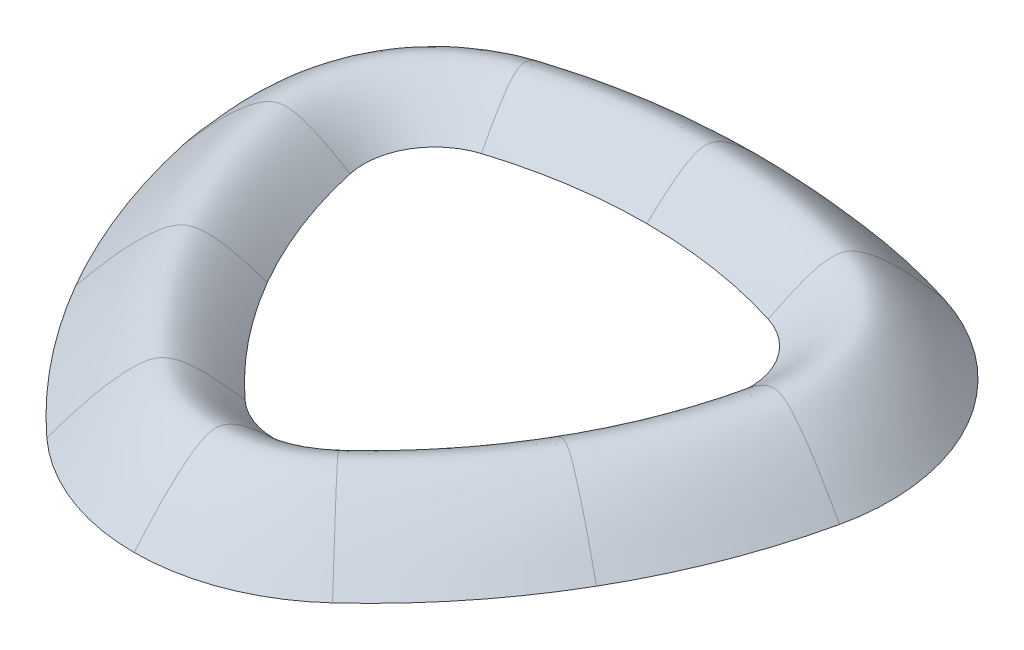
SolidWorks part; units mm, degrees
ref_plane "Plan de face" through (0, 0, 0) normal (0, 0, 1) x (1, 0, 0)
ref_plane "Plan de dessus" through (0, 0, 0) normal (0, 1, 0) x (1, 0, 0)
ref_plane "Plan de droite" through (0, 0, 0) normal (1, 0, 0) x (0, 0, -1)
ref_plane "Plan3" through (0, 110, 0) normal (0, 1, 0) x (-1, 0, 0)
ref_plane "Plan4" through (17.1, 0, 0) normal (1, 0, 0) x (0, 0, -1)
sketch "Esquisse2" plane through (0, 110, 0) normal (0, 1, 0) x (1, 0, 0)
  line L6 (-8.1531, -15.9216) -> (-19.8444, -22.6716)
  line L7 (54.0497, -22.6716) -> (42.3584, -15.9216)
  arc A10 (17.1026, 27.8226) -> (-5.1741, 24.3979) centre (17.1026, -46.3402) ccw
  arc A11 (17.1026, 41.3226) -> (-9.2291, 37.2745) centre (17.1026, -46.3402) ccw
  arc A12 (-9.2291, 37.2745) -> (-29.5045, 2.1565) centre (-0.2179, 8.6598) ccw
  arc A13 (-29.5045, 2.1565) -> (-19.8444, -22.6716) centre (56.0737, 21.1599) ccw
  arc A14 (-16.3255, 5.083) -> (-8.1531, -15.9216) centre (56.0738, 21.1598) ccw
  arc A15 (-5.1741, 24.3979) -> (-16.3255, 5.083) centre (-0.2179, 8.6598) ccw
  arc A16 (-8.1531, -15.9216) -> (5.9512, -33.5014) centre (56.0738, 21.1598) ccw
  arc A17 (-19.8444, -22.6716) -> (-3.1727, -43.4515) centre (56.0738, 21.1598) ccw
  arc A18 (-3.1727, -43.4515) -> (37.378, -43.4515) centre (17.1026, -21.3402) ccw
  arc A19 (37.378, -43.4515) -> (54.0497, -22.6716) centre (-21.8686, 21.1598) ccw
  arc A20 (28.2541, -33.5014) -> (42.3584, -15.9216) centre (-21.8685, 21.1598) ccw
  arc A21 (5.9512, -33.5014) -> (28.2541, -33.5014) centre (17.1026, -21.3402) ccw
  arc A22 (-8.1531, -15.9216) -> (5.9512, -33.5014) centre (56.0738, 21.1598) ccw
  arc A23 (-19.8444, -22.6716) -> (-3.1727, -43.4515) centre (56.0738, 21.1598) ccw
  arc A24 (-3.1727, -43.4515) -> (37.378, -43.4515) centre (17.1026, -21.3402) ccw
  arc A25 (37.378, -43.4515) -> (54.0497, -22.6716) centre (-21.8686, 21.1598) ccw
  arc A26 (28.2541, -33.5014) -> (42.3584, -15.9216) centre (-21.8685, 21.1598) ccw
  arc A27 (5.9512, -33.5014) -> (28.2541, -33.5014) centre (17.1026, -21.3402) ccw
  arc A34 (42.3584, -15.9216) -> (50.5308, 5.083) centre (-21.8685, 21.1598) ccw
  arc A35 (54.0497, -22.6716) -> (63.7098, 2.1564) centre (-21.8685, 21.1599) ccw
  arc A36 (63.7098, 2.1564) -> (43.4344, 37.2745) centre (34.4231, 8.6598) ccw
  arc A37 (43.4344, 37.2745) -> (17.1026, 41.3226) centre (17.1027, -46.3402) ccw
  arc A38 (39.3793, 24.3979) -> (17.1026, 27.8226) centre (17.1026, -46.3402) ccw
  arc A39 (50.5308, 5.083) -> (39.3793, 24.3979) centre (34.4231, 8.6598) ccw
  spline S1 degree 3 poles (17.1026, -35.3402) (17.2945, -35.3402) (17.585, -35.3335) (17.9697, -35.3151) (18.3296, -35.2878) (18.5783, -35.2628) (19.4384, -35.1634) (20.8852, -34.8799) (22.9641, -34.1179) (24.8892, -33.0438) (26.0338, -32.1454) (28.4344, -29.9441) (32.0049, -26.3034) (36.7478, -20.302) (40.7972, -13.8767) (43.0004, -9.3962) (44.4388, -6.0483) (45.2663, -3.9788) (46.3263, -0.9419) (47.2595, 2.173) (47.8205, 4.4103) (48.2248, 6.231) (48.4333, 7.5487) (48.4428, 9.8236) (48.0342, 12.2266) (47.5021, 13.7089) (46.7937, 15.2889) (45.7554, 17.0831) (43.583, 19.3997) (41.0947, 21.0774) (39.4318, 21.7603) (36.0835, 22.8148) (31.0227, 24.0976) (23.5051, 25.1675) (16.0545, 25.4426) (11.1305, 25.116) (7.5119, 24.6877) (5.3059, 24.3696) (2.1458, 23.7691) (-1.0183, 23.0198) (-3.2364, 22.387) (-5.0153, 21.8268) (-6.2607, 21.3486) (-8.2356, 20.2193) (-10.1123, 18.664) (-11.13, 17.4621) (-12.1441, 16.0585) (-13.1788, 14.2622) (-14.0988, 11.2226) (-14.3076, 8.2288) (-14.0676, 6.4472) (-13.3066, 3.0202) (-11.8871, -2.0039) (-9.0549, -9.0493) (-5.5678, -15.6392) (-2.823, -19.7403) (-0.6428, -22.66) (0.7092, -24.3765) (2.7496, -26.7512) (4.9491, -29.0929) (6.6373, -30.7387) (8.0998, -32.0796) (8.9058, -32.7376) (10.3234, -33.6134) (11.5706, -34.228) (12.9719, -34.7458) (14.4341, -35.1099) (15.8425, -35.3053) (16.6985, -35.3402) (17.1026, -35.3402) (17.2945, -35.3402) (17.585, -35.3335) knots -0.004472 0 0 0 0.002123 0.004246 0.006369 0.008493 0.008493 0.020144 0.031796 0.043448 0.0551 0.0551 0.096159 0.137217 0.178275 0.219334 0.219334 0.238889 0.258444 0.277999 0.297554 0.297554 0.307313 0.317071 0.326829 0.336587 0.336587 0.349549 0.36251 0.375472 0.388433 0.388433 0.429492 0.47055 0.511609 0.552667 0.552667 0.572222 0.591777 0.611333 0.630888 0.630888 0.640646 0.650404 0.660162 0.66992 0.66992 0.682882 0.695844 0.708805 0.721767 0.721767 0.762825 0.803884 0.844942 0.886 0.886 0.905556 0.925111 0.944666 0.964221 0.964221 0.973166 0.977638 0.982111 0.986583 0.991055 0.995528 1 1 1 1.002123 1.004246 1.006369 only from (17.1026, -35.3402) to (17.1026, -35.3402)
  spline S2 degree 3 poles (17.1026, -35.3402) (17.2945, -35.3402) (17.585, -35.3335) (17.9697, -35.3151) (18.3296, -35.2878) (18.5783, -35.2628) (19.4384, -35.1634) (20.8852, -34.8799) (22.9641, -34.1179) (24.8892, -33.0438) (26.0338, -32.1454) (28.4344, -29.9441) (32.0049, -26.3034) (36.7478, -20.302) (40.7972, -13.8767) (43.0004, -9.3962) (44.4388, -6.0483) (45.2663, -3.9788) (46.3263, -0.9419) (47.2595, 2.173) (47.8205, 4.4103) (48.2248, 6.231) (48.4333, 7.5487) (48.4428, 9.8236) (48.0342, 12.2266) (47.5021, 13.7089) (46.7937, 15.2889) (45.7554, 17.0831) (43.583, 19.3997) (41.0947, 21.0774) (39.4318, 21.7603) (36.0835, 22.8148) (31.0227, 24.0976) (23.5051, 25.1675) (16.0545, 25.4426) (11.1305, 25.116) (7.5119, 24.6877) (5.3059, 24.3696) (2.1458, 23.7691) (-1.0183, 23.0198) (-3.2364, 22.387) (-5.0153, 21.8268) (-6.2607, 21.3486) (-8.2356, 20.2193) (-10.1123, 18.664) (-11.13, 17.4621) (-12.1441, 16.0585) (-13.1788, 14.2622) (-14.0988, 11.2226) (-14.3076, 8.2288) (-14.0676, 6.4472) (-13.3066, 3.0202) (-11.8871, -2.0039) (-9.0549, -9.0493) (-5.5678, -15.6392) (-2.823, -19.7403) (-0.6428, -22.66) (0.7092, -24.3765) (2.7496, -26.7512) (4.9491, -29.0929) (6.6373, -30.7387) (8.0998, -32.0796) (8.9058, -32.7376) (10.3234, -33.6134) (11.5706, -34.228) (12.9719, -34.7458) (14.4341, -35.1099) (15.8425, -35.3053) (16.6985, -35.3402) (17.1026, -35.3402) (17.2945, -35.3402) (17.585, -35.3335) knots -0.004472 0 0 0 0.002123 0.004246 0.006369 0.008493 0.008493 0.020144 0.031796 0.043448 0.0551 0.0551 0.096159 0.137217 0.178275 0.219334 0.219334 0.238889 0.258444 0.277999 0.297554 0.297554 0.307313 0.317071 0.326829 0.336587 0.336587 0.349549 0.36251 0.375472 0.388433 0.388433 0.429492 0.47055 0.511609 0.552667 0.552667 0.572222 0.591777 0.611333 0.630888 0.630888 0.640646 0.650404 0.660162 0.66992 0.66992 0.682882 0.695844 0.708805 0.721767 0.721767 0.762825 0.803884 0.844942 0.886 0.886 0.905556 0.925111 0.944666 0.964221 0.964221 0.973166 0.977638 0.982111 0.986583 0.991055 0.995528 1 1 1 1.002123 1.004246 1.006369 only from (17.1026, -35.3402) to (17.1026, -35.3402)
  dimension "D2" = 0
  dimension "D4" = 0
sketch "Esquisse5" plane through (17.1, 0, 0) normal (-1, 0, 0) x (0, 0, 1)
  line L0 (-23.3226, 108) -> (-23.3226, 114) construction
  line L1 (-23.3226, 108) -> (-23.3226, 114)
  line L3 (-27.8226, 110) -> (-41.3226, 110)
  line L4 (-27.8226, 114) -> (-23.3226, 114) construction
  line L5 (-27.8226, 114) -> (-23.3226, 114)
  line L6 (51.3402, 110) -> (43.4515, 110) construction
  line L7 (51.3402, 110) -> (42.3402, 110)
  line L8 (37.8402, 110) -> (37.8402, 114) construction
  line L9 (37.8402, 110) -> (37.8402, 114)
  line L10 (-27.8226, 114) -> (-27.8226, 110)
  line L11 (42.3402, 114) -> (42.3402, 110)
  line L12 (42.3402, 114) -> (37.8402, 114)
  spline S0 degree 3 poles (-54903.5092, 51079.9374) (1466.9212, 138.1037) (314.7075, 473.5475) (-48.8728, 102.3988) (-50.7257, 100.4676) (-56.2112, 94.6088) (-59.7712, 90.6164) (-64.9306, 84.467) (-66.6203, 82.3903) (-69.9324, 78.1769) (-71.5567, 76.0374) (-76.2949, 69.5463) (-79.2784, 65.1194) (-84.8072, 56.0168) (-87.3535, 51.3417) (-90.7454, 44.0864) (-91.8043, 41.6272) (-93.2672, 37.8672) (-93.7345, 36.5996) (-94.6163, 34.0604) (-95.0316, 32.7869) (-96.9739, 26.3991) (-98.1012, 21.224) (-98.8575, 14.6561) (-98.976, 13.3376) (-99.1434, 10.6899) (-99.1897, 9.3604) (-101.9345, -200.5305) (529.2263, -505.3387) (-74247.296, 10639.9451) knots -12.002945 -12.002945 -12.002945 -12.002945 0.0625 0.0625 0.125 0.125 0.25 0.25 0.3125 0.3125 0.375 0.375 0.5 0.5 0.625 0.625 0.6875 0.6875 0.71875 0.71875 0.75 0.75 0.875 0.875 0.90625 0.90625 0.9375 0.9375 5.823478 5.823478 5.823478 5.823478 only from (-41.3226, 110) to (-99.1598, 0) construction
  spline S1 degree 3 poles (-41.3226, 110) (-43.2306, 108.1179) (-45.1255, 106.2242) (-48.8728, 102.3988) (-50.7257, 100.4676) (-56.2112, 94.6088) (-59.7712, 90.6164) (-64.9306, 84.467) (-66.6203, 82.3903) (-69.9324, 78.1769) (-71.5567, 76.0374) (-76.2949, 69.5463) (-79.2784, 65.1194) (-84.8072, 56.0168) (-87.3535, 51.3417) (-90.7454, 44.0864) (-91.8043, 41.6272) (-93.2672, 37.8672) (-93.7345, 36.5996) (-94.6163, 34.0604) (-95.0316, 32.7869) (-96.9739, 26.3991) (-98.1012, 21.224) (-98.8575, 14.6561) (-98.976, 13.3376) (-99.1434, 10.6899) (-99.1897, 9.3604) (-99.2421, 5.3587) (-99.1732, 2.6751) (-99.1598, 0) knots 0 0 0 0 0.0625 0.0625 0.125 0.125 0.25 0.25 0.3125 0.3125 0.375 0.375 0.5 0.5 0.625 0.625 0.6875 0.6875 0.71875 0.71875 0.75 0.75 0.875 0.875 0.90625 0.90625 0.9375 0.9375 1 1 1 1
  spline S2 degree 3 poles (-74498.6912, 8557.5283) (799.587, -513.4988) (-105.4428, -195.3689) (-97.0461, 12.7934) (-96.8063, 15.3415) (-96.0811, 20.4073) (-95.5957, 22.9251) (-94.7005, 26.6811) (-94.3743, 27.9297) (-93.6684, 30.4203) (-93.2885, 31.6628) (-91.2812, 37.8039) (-89.3211, 42.5387) (-84.8745, 51.7438) (-82.3865, 56.2133) (-78.3432, 62.7612) (-76.9432, 64.9175) (-74.7726, 68.1165) (-74.0372, 69.1772) (-72.5486, 71.2806) (-71.795, 72.3243) (-67.9828, 77.5045) (-64.7929, 81.5279) (-58.189, 89.3814) (-54.7744, 93.2111) (-49.5151, 98.8372) (-47.7389, 100.6927) (325.3347, 482.5877) (1557.7633, 120.2822) (-55711.5333, 50189.8675) knots -4.947507 -4.947507 -4.947507 -4.947507 0.0625 0.0625 0.125 0.125 0.1875 0.1875 0.21875 0.21875 0.25 0.25 0.375 0.375 0.5 0.5 0.5625 0.5625 0.59375 0.59375 0.625 0.625 0.75 0.75 0.875 0.875 0.9375 0.9375 13.85816 13.85816 13.85816 13.85816 only from (-97.1833, 2.5) to (-40.5014, 108) construction
  spline S3 degree 3 poles (-97.1833, 2.5) (-97.2144, 5.0814) (-97.253, 7.6638) (-97.0461, 12.7934) (-96.8063, 15.3415) (-96.0811, 20.4073) (-95.5957, 22.9251) (-94.7005, 26.6811) (-94.3743, 27.9297) (-93.6684, 30.4203) (-93.2885, 31.6628) (-91.2812, 37.8039) (-89.3211, 42.5387) (-84.8745, 51.7438) (-82.3865, 56.2133) (-78.3432, 62.7612) (-76.9432, 64.9175) (-74.7726, 68.1165) (-74.0372, 69.1772) (-72.5486, 71.2806) (-71.795, 72.3243) (-67.9828, 77.5045) (-64.7929, 81.5279) (-58.189, 89.3814) (-54.7744, 93.2111) (-49.5151, 98.8372) (-47.7389, 100.6927) (-44.147, 104.3695) (-42.3309, 106.1905) (-40.5014, 108) knots 0 0 0 0 0.0625 0.0625 0.125 0.125 0.1875 0.1875 0.21875 0.21875 0.25 0.25 0.375 0.375 0.5 0.5 0.5625 0.5625 0.59375 0.59375 0.625 0.625 0.75 0.75 0.875 0.875 0.9375 0.9375 1 1 1 1
  spline S4 degree 3 poles (-22537.6569, 3746.396) (23137.337, -5789.8364) (-22726.1069, 7123.5089) (21886.5654, -7097.5824) knots -6.815675 -6.815675 -6.815675 -6.815675 8.191972 8.191972 8.191972 8.191972 only from (81.2122, 68.474) to (51.3402, 110) construction
  spline S5 degree 3 poles (81.2122, 68.474) (71.4487, 84.3158) (60.053, 98.5496) (51.3402, 110) knots 0.568865 0.568865 0.568865 0.568865 1 1 1 1
  spline S6 degree 3 poles (19684.3579, 12060.5778) (115.0555, -173.1198) (138.2853, -24.6122) (77.1646, 71.1542) (76.3878, 72.3575) (75.6044, 73.5564) (74.3649, 75.4317) (72.6518, 77.9713) (70.458, 81.1375) (68.2449, 84.2572) (65.3179, 88.2993) (62.3347, 92.3126) (59.2835, 96.3437) (56.8088, 99.5837) (-232.854, 476.3179) (-439.167, 915.3554) (-18934.1788, -12683.5829) knots -6.945927 -6.945927 -6.945927 -6.945927 0.029562 0.059123 0.088682 0.118246 0.147807 0.227866 0.307928 0.386315 0.464703 0.616942 0.695939 0.777753 0.869386 30.121567 30.121567 30.121567 30.121567 only from (78.6967, 68.7339) to (50.3497, 108) construction
  spline S7 degree 3 poles (78.6967, 68.7339) (78.4429, 69.1383) (77.9352, 69.9469) (77.1646, 71.1542) (76.3878, 72.3575) (75.6044, 73.5564) (74.3649, 75.4317) (72.6518, 77.9713) (70.458, 81.1375) (68.2449, 84.2572) (65.3179, 88.2993) (62.3347, 92.3126) (59.2835, 96.3437) (56.8088, 99.5837) (53.8157, 103.4766) (51.6326, 106.3256) (50.3497, 108) knots 0 0 0 0 0.029562 0.059123 0.088682 0.118246 0.147807 0.227866 0.307928 0.386315 0.464703 0.616942 0.695939 0.777753 0.869386 1 1 1 1
  spline S8 degree 3 poles (51.3402, 110) (47.1474, 115.243) (46.1407, 115.7153) (42.0983, 118.9716) (37.3879, 120.4746) (37.8402, 114) knots 0 0 0 0 0.450652 0.528749 1 1 1 1
  dimension "D1" = 4.5
ref_plane "Plan1" through (17.1, 0, 0) normal (1, 0, 0) x (0, 0, -1)
sketch "Esquisse6" plane through (17.1, 0, 0) normal (1, 0, 0) x (0, 0, -1)
  line L1 (-37.8402, 114) -> (-31.4344, 114.0343)
  line L3 (-37.8402, 114) -> (-37.8402, 110)
  line L4 (-51.3402, 110) -> (-42.3402, 110) construction
  line L5 (-51.3402, 110) -> (-37.8402, 110)
  spline S1 degree 3 poles (-51.3402, 110) (-49.3119, 112.2932) (-46.168, 116.1399) (-41.0032, 119.6289) (-37.5171, 119.3638) (-34.664, 117.098) (-31.4344, 114.0343) knots 0 0 0 0 0.461578 0.652296 0.706138 1 1 1 1
ref_plane "Plan2" through (0, 110, 0) normal (0, 1, 0) x (-1, 0, 0)
sketch "Esquisse7" plane through (0, 110, 0) normal (0, 1, 0) x (-1, 0, 0)
  arc A0 (3.1727, 43.4515) -> (-37.378, 43.4515) centre (-17.1026, 21.3402) ccw construction
  arc A1 (3.1727, 43.4515) -> (-37.378, 43.4515) centre (-17.1026, 21.3402) ccw
  arc A2 (-37.378, 43.4515) -> (-54.0497, 22.6716) centre (21.8686, -21.1598) ccw construction
  arc A3 (-37.378, 43.4515) -> (-54.0497, 22.6716) centre (21.8686, -21.1598) ccw
  arc A4 (-54.0497, 22.6716) -> (-63.7098, -2.1564) centre (21.8685, -21.1599) ccw construction
  arc A5 (-54.0497, 22.6716) -> (-63.7098, -2.1564) centre (21.8685, -21.1599) ccw
  arc A6 (-63.7098, -2.1564) -> (-43.4344, -37.2745) centre (-34.4231, -8.6598) ccw construction
  arc A7 (-63.7098, -2.1564) -> (-43.4344, -37.2745) centre (-34.4231, -8.6598) ccw
  arc A8 (-43.4344, -37.2745) -> (-17.1026, -41.3226) centre (-17.1027, 46.3402) ccw construction
  arc A9 (-43.4344, -37.2745) -> (-17.1026, -41.3226) centre (-17.1027, 46.3402) ccw
  arc A10 (-17.1026, -41.3226) -> (9.2291, -37.2745) centre (-17.1026, 46.3402) ccw construction
  arc A11 (-17.1026, -41.3226) -> (9.2291, -37.2745) centre (-17.1026, 46.3402) ccw
  arc A12 (9.2291, -37.2745) -> (29.5045, -2.1565) centre (0.2179, -8.6598) ccw construction
  arc A13 (9.2291, -37.2745) -> (29.5045, -2.1565) centre (0.2179, -8.6598) ccw
  arc A14 (29.5045, -2.1565) -> (19.8444, 22.6716) centre (-56.0737, -21.1599) ccw construction
  arc A15 (29.5045, -2.1565) -> (19.8444, 22.6716) centre (-56.0737, -21.1599) ccw
  arc A16 (19.8444, 22.6716) -> (3.1727, 43.4515) centre (-56.0738, -21.1598) ccw construction
  arc A17 (19.8444, 22.6716) -> (3.1727, 43.4515) centre (-56.0738, -21.1598) ccw
sweep "Balayage1" add profiles "Esquisse6" path "Esquisse7"
